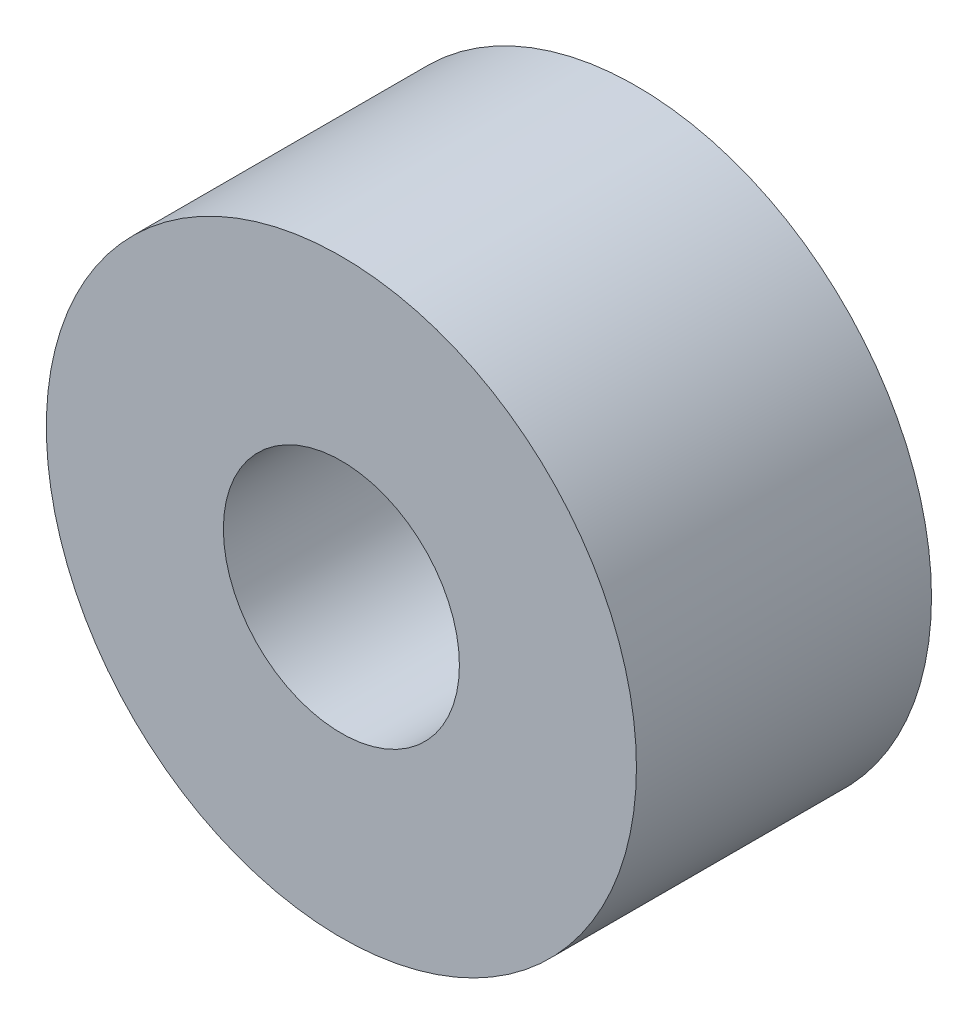
SolidWorks part; units mm, degrees
ref_plane "前视基准面" through (0, 0, 0) normal (0, 0, 1) x (1, 0, 0)
ref_plane "上视基准面" through (0, 0, 0) normal (0, 1, 0) x (1, 0, 0)
ref_plane "右视基准面" through (0, 0, 0) normal (1, 0, 0) x (0, 0, -1)
sketch "草图1" plane through (0, 0, 0) normal (0, 0, 1) x (1, 0, 0)
  circle A0 centre (0, 0) radius 1
  circle A1 centre (0, 0) radius 2.5
  dimension "D1" = 2
  dimension "D2" = 5
extrude "凸台-拉伸1" add sketch "草图1" along normal blind 2.5
